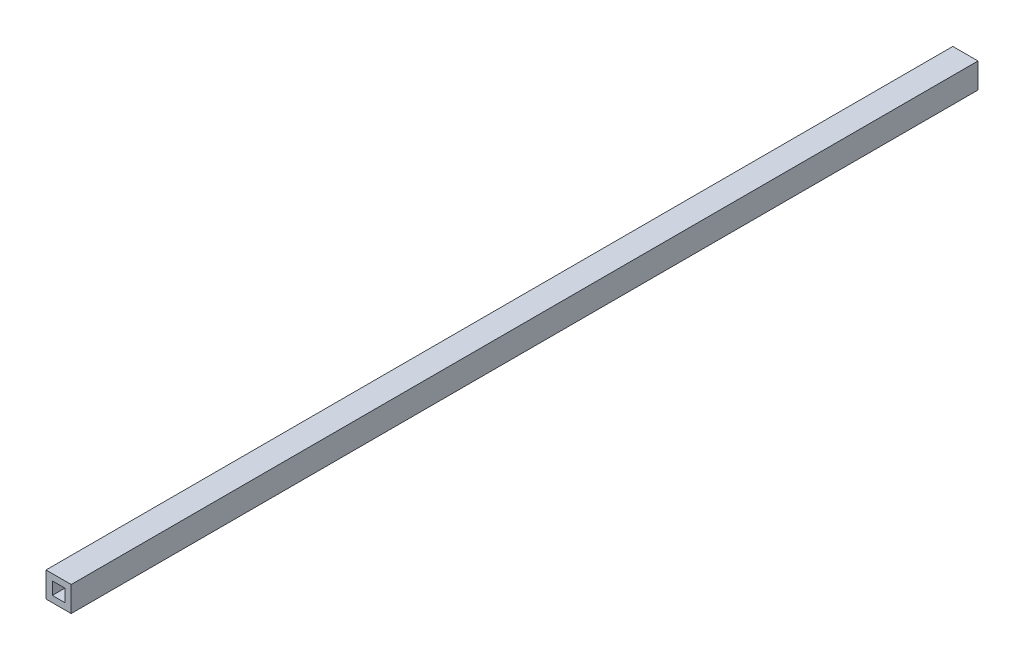
SolidWorks part; units mm, degrees
ref_plane "Front Plane" through (0, 0, 0) normal (0, 0, 1) x (1, 0, 0)
ref_plane "Top Plane" through (0, 0, 0) normal (0, 1, 0) x (1, 0, 0)
ref_plane "Right Plane" through (0, 0, 0) normal (1, 0, 0) x (0, 0, -1)
sketch "Sketch1" plane through (0, 0, 0) normal (1, 0, 0) x (0, 0, -1)
  line L1 (457.2, -12.7) -> (-457.2, -12.7)
  line L2 (457.2, -12.7) -> (457.2, 12.7)
  line L3 (457.2, 12.7) -> (-457.2, 12.7)
  line L4 (-457.2, -12.7) -> (-457.2, 12.7)
  line L5 (457.2, -12.7) -> (-457.2, 12.7) construction
  line L6 (457.2, 12.7) -> (-457.2, -12.7) construction
  point P0 (0, 0)
  point P6 (0, 0)
  dimension "D1" = 914.4
  dimension "D2" = 25.4
extrude "Boss-Extrude1" add sketch "Sketch1" along normal blind 25.4
sketch "Sketch2" plane through (0, 0, 457.2) normal (0, 0, 1) x (1, 0, 0)
  line L1 (6.35, -6.35) -> (19.05, -6.35)
  line L2 (6.35, -6.35) -> (6.35, 6.35)
  line L3 (6.35, 6.35) -> (19.05, 6.35)
  line L4 (19.05, -6.35) -> (19.05, 6.35)
  line L5 (6.35, -6.35) -> (19.05, 6.35) construction
  line L6 (6.35, 6.35) -> (19.05, -6.35) construction
  point P0 (12.7, 0)
  point P5 (0, 0)
  dimension "D1" = 12.7
  dimension "D2" = 12.7
extrude "Cut-Extrude1" cut sketch "Sketch2" against normal through all
